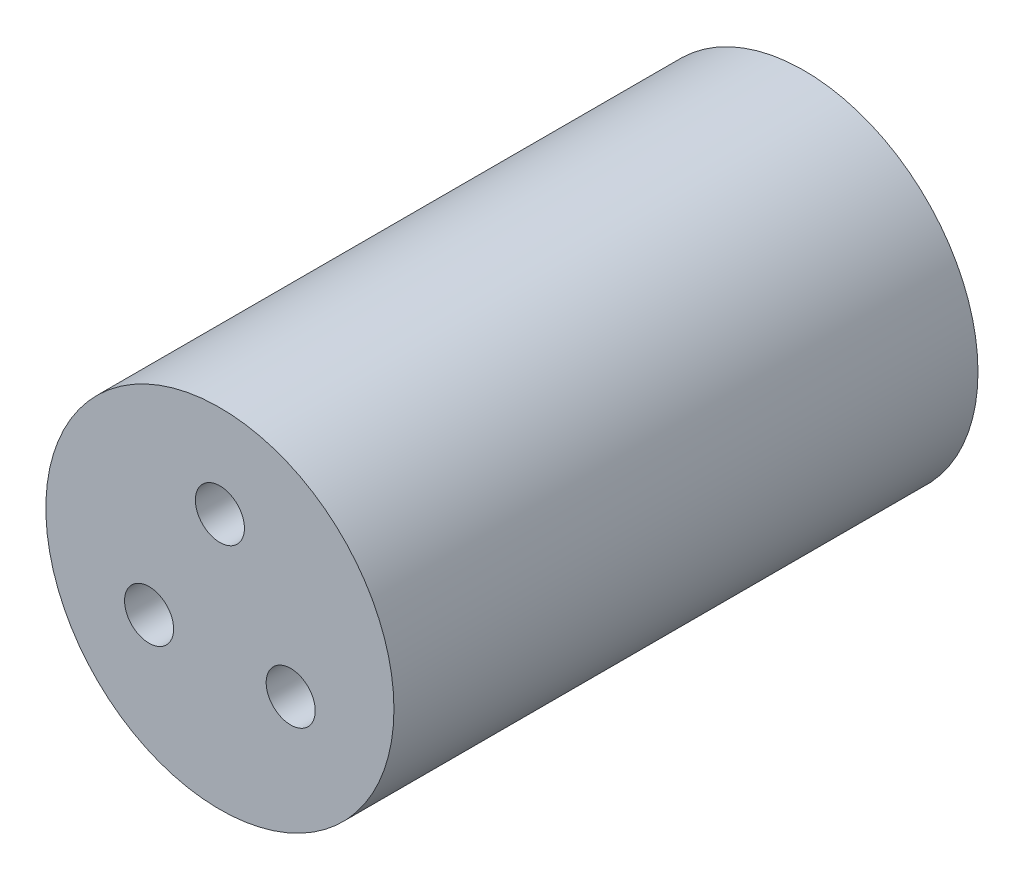
SolidWorks part; units mm, degrees
ref_plane "Front Plane" through (0, 0, 0) normal (0, 0, 1) x (1, 0, 0)
ref_plane "Top Plane" through (0, 0, 0) normal (0, 1, 0) x (1, 0, 0)
ref_plane "Right Plane" through (0, 0, 0) normal (1, 0, 0) x (0, 0, -1)
sketch "Sketch2" plane through (0, 0, 0) normal (0, 0, 1) x (1, 0, 0)
  line L0 (0, 0) -> (0, 7) construction
  circle A0 centre (0, 0) radius 14.9
  circle A1 centre (0, 7) radius 1.7
  circle A2 centre (6.0622, -3.5) radius 1.7
  circle A3 centre (-6.0622, -3.5) radius 1.7
  point P6 (7.9249, -3.0975)
  point P7 (0, 0)
  point P11 (0, 0)
  dimension "D1" = 29.8
  dimension "D3" = 3.4
  dimension "D2" = 7
  dimension "D4" = 3
extrude "Boss-Extrude1" add sketch "Sketch2" along normal blind 50
sketch "Sketch3" plane through (0, 0, 50) normal (0, 0, 1) x (1, 0, 0)
  circle A0 centre (0, 7) radius 2.1
  circle A1 centre (6.0622, -3.5) radius 2.1
  circle A2 centre (-6.0622, -3.5) radius 2.1
  dimension "D1" = 4.2
  dimension "D2" = 4.2
  dimension "D3" = 4.2
extrude "Cut-Extrude1" cut sketch "Sketch3" against normal blind 5.7
ref_plane "Plane1" through (0, 0, 25) normal (0, 0, 1) x (1, 0, 0)
mirror "Mirror1" about plane through (0, 0, 25) normal (0, 0, 1) of "Cut-Extrude1"
